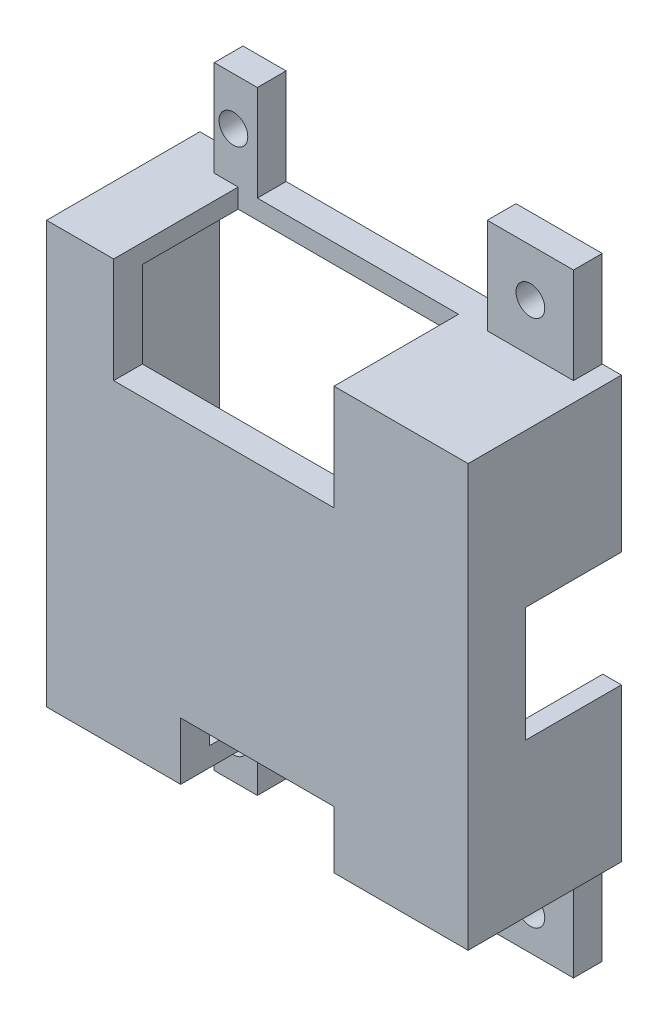
SolidWorks part; units mm, degrees
ref_plane "Front Plane" through (0, 0, 0) normal (0, 0, 1) x (1, 0, 0)
ref_plane "Top Plane" through (0, 0, 0) normal (0, 1, 0) x (1, 0, 0)
ref_plane "Right Plane" through (0, 0, 0) normal (1, 0, 0) x (0, 0, -1)
sketch "Sketch1" plane through (0, 0, 0) normal (0, 0, 1) x (1, 0, 0)
  line L0 (0, 0) -> (44, 0)
  line L1 (44, 0) -> (44, 44)
  line L2 (44, 44) -> (0, 44)
  line L3 (0, 44) -> (0, 0)
  dimension "D1" = 44
  dimension "D2" = 44
extrude "Boss-Extrude1" add sketch "Sketch1" along normal blind 16
sketch "Sketch3" plane through (0, 0, 0) normal (0, 0, -1) x (-1, 0, 0)
  line L1 (-42.0638, 42) -> (-2.0638, 42)
  line L2 (-42.0638, 42) -> (-42.0638, 2)
  line L3 (-42.0638, 2) -> (-2.0638, 2)
  line L4 (-2.0638, 42) -> (-2.0638, 2)
  dimension "D1" = 40
  dimension "D2" = 40
  dimension "D3" = 2
  dimension "D4" = 2
  dimension "D5" = 2
  dimension "D6" = 2
extrude "Cut-Extrude1" cut sketch "Sketch3" against normal blind 13
ref_plane "Plane1" through (0, 44, 16) normal (-1, 0, 0) x (0, 0, 1)
sketch "Sketch5" plane through (0, 0, 16) normal (0, 0, 1) x (1, 0, 0)
  line L0 (0, 44) -> (0, 0) construction
  line L1 (7, 44) -> (30, 44)
  line L2 (7, 44) -> (7, 33)
  line L3 (7, 33) -> (30, 33)
  line L4 (30, 44) -> (30, 33)
  dimension "D1" = 0
  dimension "D2" = 7
  dimension "D3" = 14
  dimension "D4" = 11
extrude "Cut-Extrude2" cut sketch "Sketch5" against normal blind 13
sketch "Sketch6" plane through (0, 0, 16) normal (0, 0, 1) x (1, 0, 0)
  line L0 (0, 0) -> (44, 0) construction
  line L1 (14, 6) -> (30, 6)
  line L2 (14, 6) -> (14, 0)
  line L3 (14, 0) -> (30, 0)
  line L4 (30, 6) -> (30, 0)
  dimension "D1" = 14
  dimension "D2" = 14
  dimension "D3" = 6
extrude "Cut-Extrude3" cut sketch "Sketch6" against normal blind 10
sketch "Sketch7" plane through (44, 0, 0) normal (1, 0, 0) x (0, 0, -1)
  line L0 (0, 0) -> (0, 44) construction
  line L1 (0, 16) -> (-10, 16)
  line L2 (0, 16) -> (0, 28)
  line L3 (0, 28) -> (-10, 28)
  line L4 (-10, 16) -> (-10, 28)
  dimension "D1" = 16
  dimension "D2" = 16
  dimension "D3" = 10
extrude "Cut-Extrude4" cut sketch "Sketch7" against normal blind 5
sketch "Sketch8" plane through (0, 0, 0) normal (0, -1, 0) x (-1, 0, 0)
  line L0 (0, 0) -> (-44, 0) construction
  line L1 (-4.5, -3) -> (-9, -3)
  line L2 (-4.5, -3) -> (-4.5, 0)
  line L3 (-4.5, 0) -> (-9, 0)
  line L4 (-9, -3) -> (-9, 0)
  line L6 (-33, -3) -> (-42, -3)
  line L7 (-33, -3) -> (-33, 0)
  line L8 (-33, 0) -> (-42, 0)
  line L9 (-42, -3) -> (-42, 0)
  dimension "D1" = 3
  dimension "D2" = 24
  dimension "D3" = 4.5
  dimension "D4" = 9
  dimension "D5" = 3
  dimension "D6" = 9
extrude "Boss-Extrude2" add sketch "Sketch8" along normal blind 10
sketch "Sketch9" plane through (0, 0, 3) normal (0, 0, 1) x (1, 0, 0)
  line L0 (33, -10) -> (33, 0) construction
  circle A0 centre (6.5, -6.0773) radius 1.5
  circle A1 centre (37.5, -6.0773) radius 1.5
  dimension "D2" = 3
  dimension "D3" = 3
  dimension "D1" = 31
  dimension "D4" = 4.5
extrude "Cut-Extrude5" cut sketch "Sketch9" against normal blind 10
sketch "Sketch10" plane through (0, 44, 0) normal (0, 1, 0) x (1, 0, 0)
  line L0 (44, 0) -> (0, 0) construction
  line L1 (42, 0) -> (33, 0)
  line L2 (42, 0) -> (42, -3)
  line L3 (42, -3) -> (33, -3)
  line L4 (33, 0) -> (33, -3)
  line L6 (9, 0) -> (4.5, 0)
  line L7 (9, 0) -> (9, -3)
  line L8 (9, -3) -> (4.5, -3)
  line L9 (4.5, 0) -> (4.5, -3)
  dimension "D1" = 3
  dimension "D2" = 3
  dimension "D3" = 9
  dimension "D4" = 24
  dimension "D5" = 4.5
  dimension "D6" = 9
extrude "Boss-Extrude3" add sketch "Sketch10" along normal blind 10
sketch "Sketch11" plane through (0, 0, 3) normal (0, 0, 1) x (1, 0, 0)
  line L0 (42, 54) -> (42, 44) construction
  circle A0 centre (37.5, 49.0313) radius 1.5
  circle A1 centre (6.5, 49.0313) radius 1.5
  dimension "D3" = 3
  dimension "D4" = 3
  dimension "D1" = 31
  dimension "D2" = 4.5
extrude "Cut-Extrude6" cut sketch "Sketch11" against normal blind 10
